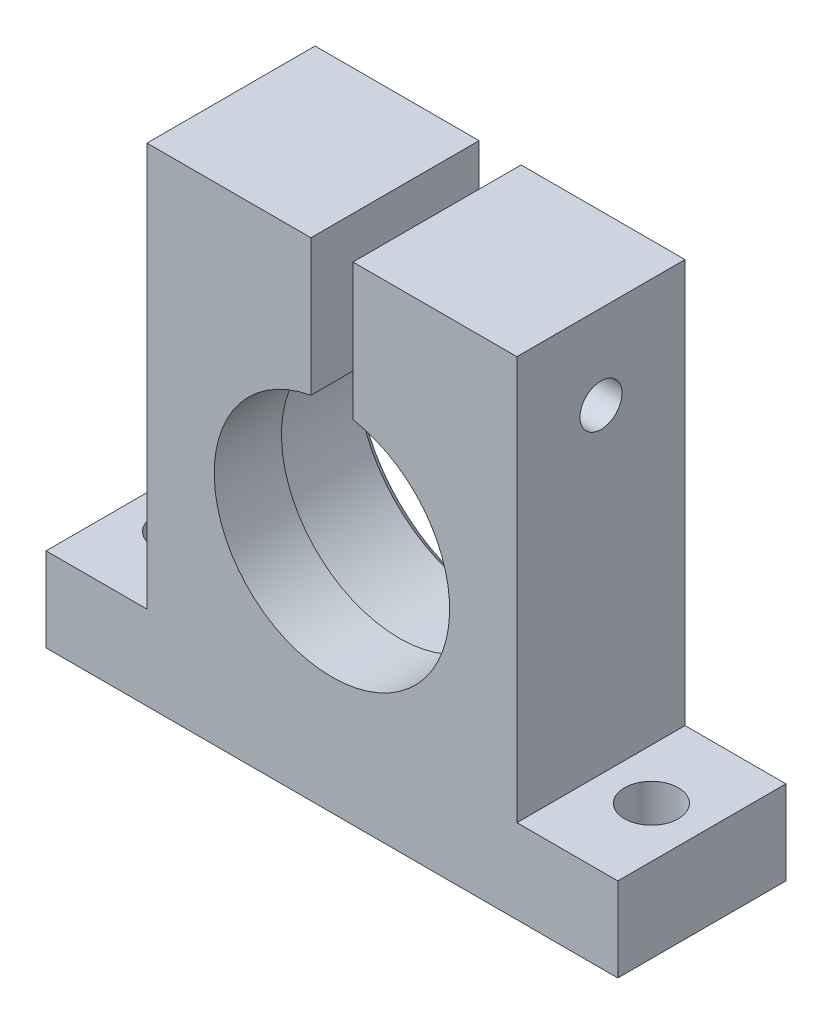
SolidWorks part; units mm, degrees
material "AISI 1045 Steel, cold drawn"
ref_plane "Front Plane" through (0, 0, 0) normal (0, 0, 1) x (1, 0, 0)
ref_plane "Top Plane" through (0, 0, 0) normal (0, 1, 0) x (1, 0, 0)
ref_plane "Right Plane" through (0, 0, 0) normal (1, 0, 0) x (0, 0, -1)
sketch "Sketch1" plane through (0, 0, 0) normal (0, 0, 1) x (1, 0, 0)
  line L1 (11, -14) -> (-11, -14)
  line L2 (11, -14) -> (11, 15)
  line L3 (11, 15) -> (-11, 15)
  line L4 (-11, -14) -> (-11, 15)
  line L5 (11, -14) -> (-11, 15) construction
  line L6 (11, 15) -> (-11, -14) construction
  circle A0 centre (0, 0) radius 8 construction
  point P3 (0, 0.5)
  dimension "D1" = 16
  dimension "D2" = 29
  dimension "D3" = 15
  dimension "D4" = 22
extrude "Boss-Extrude1" add sketch "Sketch1" along normal mid plane 10
sketch "Sketch3" plane through (0, -14, 0) normal (0, -1, 0) x (1, 0, 0)
  line L0 (-11, 5) -> (11, 5) construction
  line L1 (17, -5) -> (-17, -5)
  line L2 (17, -5) -> (17, 5)
  line L3 (17, 5) -> (-17, 5)
  line L4 (-17, -5) -> (-17, 5)
  line L5 (17, -5) -> (-17, 5) construction
  line L6 (17, 5) -> (-17, -5) construction
  point P0 (0, 0)
  dimension "D1" = 34
extrude "Boss-Extrude2" add sketch "Sketch3" against normal blind 5
hole_wizard "Ø16.0 (16) Diameter Hole1" positions "Sketch4" profile "Sketch5" hole size "Ø16.0" standard "ANSI Metric"
sketch "Sketch4" plane through (0, 0, -5) normal (0, 0, -1) x (-1, 0, 0)
  point P0 (0, 0)
sketch "Sketch5" plane through (0, 0, -5) normal (1, 0, 0) x (0, 1, 0)
  line L0 (0, 0) -> (0, 6)
  line L1 (0, 6) -> (8, 6)
  line L2 (8, 6) -> (8, 0)
  line L5 (8, 0) -> (0, 0)
  line L10 (0, 6) -> (-8, 6) construction
  line L11 (0, -6.35) -> (0, 107.95) construction
  dimension "Hole Dia." = 16
  dimension "Hole Depth" = 6
  dimension "Drill Angle" = 180
hole_wizard "Ø14.0 (14) Diameter Hole1" positions "Sketch13" profile "Sketch14" hole size "Ø14.0" standard "ANSI Metric" end condition through all
sketch "Sketch13" plane through (0, 0, 1) normal (0, 0, -1) x (-1, 0, 0)
  point P0 (0, 0)
sketch "Sketch14" plane through (0, 0, 1) normal (1, 0, 0) x (0, 1, 0)
  line L0 (0, 0) -> (0, 4)
  line L1 (0, 4) -> (7, 4)
  line L2 (7, 4) -> (7, 0)
  line L5 (7, 0) -> (0, 0)
  line L11 (0, -6.35) -> (0, 107.95) construction
  dimension "Thru Hole Dia." = 14
  dimension "Thru Hole Depth" = 4
hole_wizard "M3 Clearance Hole1" positions "Sketch6" profile "Sketch7" hole size "M3" standard "ANSI Metric" end condition through all
sketch "Sketch6" plane through (0, -9, 0) normal (0, 1, 0) x (1, 0, 0)
  line L0 (-17, -5) -> (-11, 5) construction
  line L2 (17, -5) -> (11, 5) construction
  point P0 (-14, 0)
  point P2 (14, 0)
sketch "Sketch7" plane through (-14, -9, 0) normal (1, 0, 0) x (0, 0, 1)
  line L0 (0, 0) -> (0, 5)
  line L1 (0, 5) -> (1.6, 5)
  line L2 (1.6, 5) -> (1.6, 0)
  line L5 (1.6, 0) -> (0, 0)
  line L11 (0, -6.35) -> (0, 107.95) construction
  dimension "Thru Hole Dia." = 3.2
  dimension "Thru Hole Depth" = 5
sketch "Sketch12" plane through (0, 0, 5) normal (0, 0, 1) x (1, 0, 0)
  line L0 (11, 15) -> (-11, 15) construction
  line L1 (1.25, 6.8875) -> (-1.25, 6.8875)
  line L2 (1.25, 6.8875) -> (1.25, 15)
  line L3 (1.25, 15) -> (-1.25, 15)
  line L4 (-1.25, 6.8875) -> (-1.25, 15)
  line L5 (1.25, 6.8875) -> (-1.25, 15) construction
  line L6 (1.25, 15) -> (-1.25, 6.8875) construction
  circle A1 centre (0, 0) radius 7 construction
  point P0 (0, 10.9437)
  dimension "D1" = 2.5
extrude "Cut-Extrude1" cut sketch "Sketch12" against normal through all
hole_wizard "CBORE for M3 SHCS1" positions "Sketch10" profile "Sketch11" counterbore size "M3" standard "ANSI Metric"
sketch "Sketch10" plane through (11, 0, 0) normal (1, 0, 0) x (0, 0, -1)
  line L0 (-5, 15) -> (5, 15) construction
  point P0 (0, 10)
  point P4 (0, 0)
  point P7 (0, 0)
  dimension "D1" = 5
sketch "Sketch11" plane through (11, 10, 0) normal (0, 1, 0) x (0, 0, -1)
  line L0 (0, 0) -> (0, 9.75)
  line L1 (0, 9.75) -> (1.6, 9.75)
  line L3 (1.6, 9.75) -> (1.6, 3)
  line L4 (1.6, 3) -> (3.25, 3)
  line L5 (3.25, 3) -> (3.25, 0)
  line L7 (3.25, 0) -> (0, 0)
  line L11 (0, -6.35) -> (0, 107.95) construction
  dimension "Thru Hole Dia." = 3.2
  dimension "Thru Hole Depth" = 9.75
  dimension "C'Bore Dia." = 6.5
  dimension "C'Bore Depth" = 3
chamfer "Chamfer1" distance 0.5 angle 45 1 edges at (0, -8, -5)
mirror "Mirror1" about plane through (-17, -9, -5) normal (-1, 0, 0) of bodies 106
delete or keep bodies "Body-Delete/Keep 1" type delete bodies bodies 106
hole_wizard "M3x0.5 Tapped Hole1" positions "Sketch15" profile "Sketch16" tap size "M3x0.5" standard "ANSI Metric" end condition up to next
sketch "Sketch15" plane through (-23, 0, 0) normal (1, 0, 0) x (0, 0, -1)
  circle A0 centre (0, 10) radius 1.6 construction
  point P0 (0, 10)
  point P5 (0, 0)
cosmetic thread "Hole Thread5" parameters "D2"=3
sketch "Sketch16" plane through (-23, 10, 0) normal (0, 1, 0) x (0, 0, -1)
  line L0 (0, 0) -> (0, 9.75)
  line L1 (0, 9.75) -> (1.25, 9.75)
  line L2 (1.25, 9.75) -> (1.25, 0)
  line L5 (1.25, 0) -> (0, 0)
  line L11 (0, -6.35) -> (0, 107.95) construction
  dimension "Thru Tap Drill Dia." = 2.5
  dimension "Thru Tap Drill Depth" = 9.75
